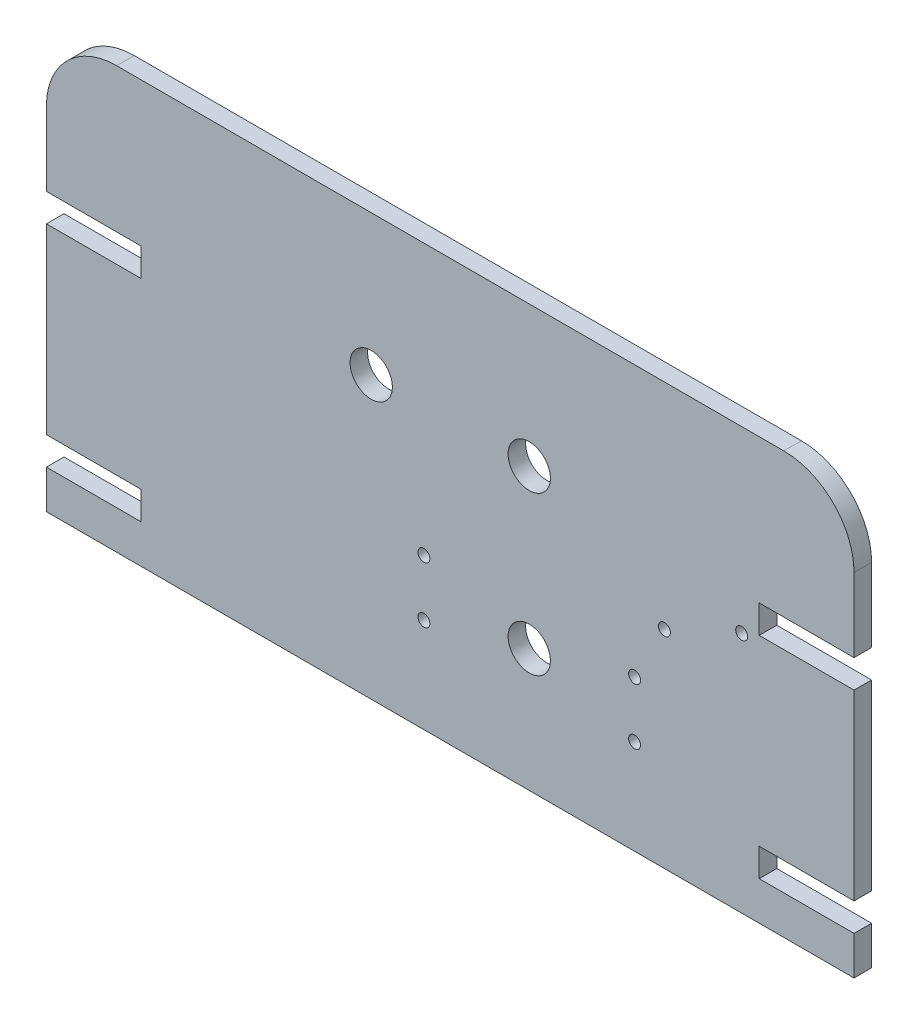
SolidWorks part; units mm, degrees
ref_plane "Front Plane" through (0, 0, 0) normal (0, 0, 1) x (1, 0, 0)
ref_plane "Top Plane" through (0, 0, 0) normal (0, 1, 0) x (1, 0, 0)
ref_plane "Right Plane" through (0, 0, 0) normal (1, 0, 0) x (0, 0, -1)
sketch "Sketch1" plane through (0, 0, 0) normal (0, 0, 1) x (1, 0, 0)
  line L1 (-115, -60) -> (115, -60)
  line L2 (-115, -60) -> (-115, 60)
  line L3 (-115, 60) -> (115, 60)
  line L4 (115, -60) -> (115, 60)
  line L5 (-115, -60) -> (115, 60) construction
  line L6 (-115, 60) -> (115, -60) construction
  point P0 (0, 0)
  dimension "D1" = 230
  dimension "D2" = 120
extrude "Boss-Extrude1" add sketch "Sketch1" along normal blind 5
sketch "Sketch2" plane through (0, 0, 0) normal (0, 0, -1) x (-1, 0, 0)
  line L0 (115, 11) -> (88, 11)
  line L1 (115, 60) -> (115, -60) construction
  line L2 (88, 11) -> (88, 19)
  line L3 (88, 19) -> (115, 19)
  line L4 (115, 19) -> (115, 11)
  line L5 (117.8, 19) -> (115.5, 19) construction
  line L6 (115.5, 11) -> (117.8, 11) construction
  line L7 (115, -49) -> (88, -49)
  line L8 (88, -41) -> (115, -41)
  line L9 (88, -49) -> (88, -41)
  line L10 (115, -41) -> (115, -49)
  line L11 (115.5, -49) -> (117.8, -49) construction
  line L12 (117.8, -41) -> (115.5, -41) construction
  line L13 (115, -40.5) -> (115, -30.5) construction
  line L14 (0, 2.75) -> (0, -2.75) construction
  line L15 (-115, -41) -> (-115, -49)
  line L16 (-88, -49) -> (-88, -41)
  line L17 (-88, -41) -> (-115, -41)
  line L18 (-115, -49) -> (-88, -49)
  line L19 (-115, 19) -> (-115, 11)
  line L20 (-88, 19) -> (-115, 19)
  line L21 (-88, 11) -> (-88, 19)
  line L22 (-115, 11) -> (-88, 11)
  dimension "D1" = 27
  dimension "D2" = 27
extrude "Cut-Extrude1" cut sketch "Sketch2" against normal up to next
sketch "Sketch3" plane through (0, 0, 5) normal (0, 0, 1) x (1, 0, 0)
  line L0 (-115, 20) -> (115, 20) construction
  line L1 (-115, 60) -> (-115, 19) construction
  line L2 (115, 19) -> (115, 60) construction
  line L3 (115, 60) -> (-115, 60) construction
  line L4 (22.5, 60) -> (22.5, -60) construction
  line L5 (-115, -60) -> (115, -60) construction
  circle A0 centre (22.5, 20) radius 6.025
  circle A1 centre (-22.5, 20) radius 6.025
  circle A2 centre (22.5, -25) radius 6.025
  dimension "D2" = 12.05
  dimension "D3" = 45
  dimension "D1" = 40
  dimension "D4" = 45
  dimension "D5" = 22.5
extrude "Cut-Extrude2" cut sketch "Sketch3" against normal up to next
sketch "Sketch5" plane through (0, 0, 5) normal (0, 0, 1) x (1, 0, 0)
  line L1 (-7.5, -33) -> (52.5, -33)
  line L2 (-7.5, -33) -> (-7.5, -17)
  line L3 (-7.5, -17) -> (52.5, -17)
  line L4 (52.5, -33) -> (52.5, -17)
  line L5 (-7.5, -33) -> (52.5, -17) construction
  line L6 (-7.5, -17) -> (52.5, -33) construction
  point P0 (22.5, -25)
  dimension "D1" = 16
  dimension "D2" = 60
hole_wizard "M3 Clearance Hole1" positions "3DSketch1" profile "Sketch6" hole size "M3" standard "ISO" end condition through all
sketch3d "3DSketch1"
  point P0 (-7.5, -17, 5)
  point P3 (52.5, -17, 5)
  point P6 (52.5, -33, 5)
  point P9 (-7.5, -33, 5)
sketch "Sketch6" plane through (-7.5, -17, 5) normal (1, 0, 0) x (0, -1, 0)
  line L0 (0, 0) -> (0, 5)
  line L1 (0, 5) -> (1.7, 5)
  line L2 (1.7, 5) -> (1.7, 0)
  line L5 (1.7, 0) -> (0, 0)
  line L11 (0, -6.35) -> (0, 107.95) construction
  dimension "Thru Hole Dia." = 3.4
  dimension "Thru Hole Depth" = 5
fillet "Fillet1" radius 20 2 edges at (115, 60, 2.5) (-115, 60, 2.5)
sketch "Sketch7" plane through (0, 0, 5) normal (0, 0, 1) x (1, 0, 0)
  line L0 (83, 9) -> (83, -1) construction
  line L1 (83, -1) -> (61, -1) construction
  line L2 (61, -1) -> (83, 9) construction
  line L3 (115, -41) -> (115, 11) construction
  line L4 (88, 11) -> (115, 11) construction
  circle A0 centre (61, -1) radius 1.7
  circle A1 centre (83, 9) radius 1.7
  point P1 (61, -1)
  point P3 (83, 9)
  dimension "D5" = 3.4
  dimension "D1" = 10
  dimension "D2" = 22
  dimension "D3" = 32
  dimension "D4" = 12
extrude "Cut-Extrude3" cut sketch "Sketch7" against normal up to next
